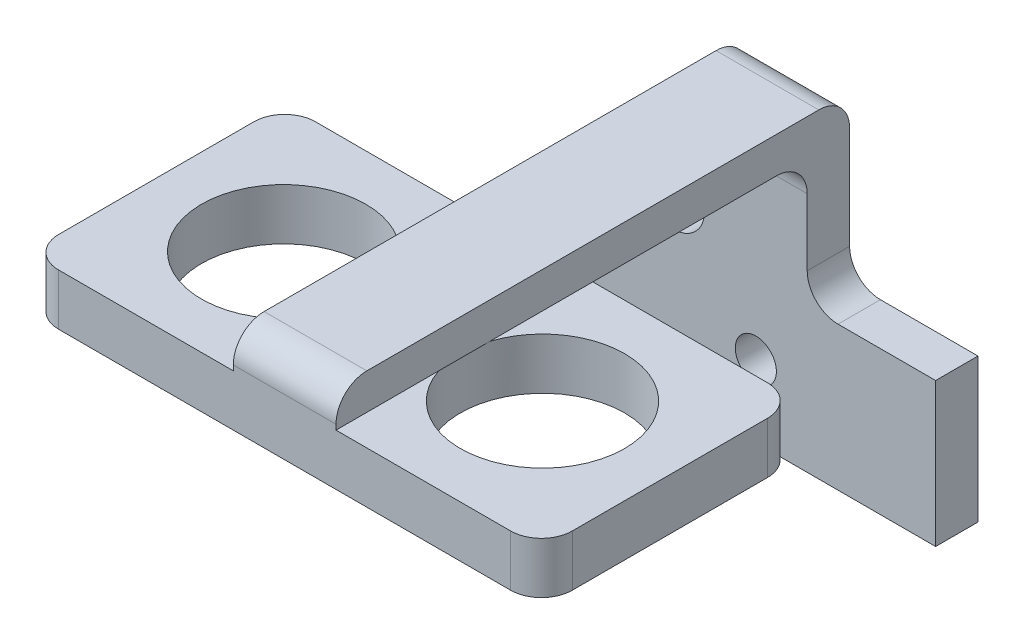
SolidWorks part; units mm, degrees
ref_plane "Front Plane" through (0, 0, 0) normal (0, 0, 1) x (1, 0, 0)
ref_plane "Top Plane" through (0, 0, 0) normal (0, 1, 0) x (1, 0, 0)
ref_plane "Right Plane" through (0, 0, 0) normal (1, 0, 0) x (0, 0, -1)
ref_plane "Plane1" through (0, -5, 0) normal (0, -1, 0) x (1, 0, 0)
sketch "Sketch1" plane through (0, -5, 0) normal (0, -1, 0) x (1, 0, 0)
  line L0 (-25, 12.5) -> (-25, -12.5)
  line L1 (-25, -12.5) -> (25, -12.5)
  line L2 (25, -12.5) -> (25, 12.5)
  line L3 (25, 12.5) -> (-25, 12.5)
extrude "Boss-Extrude1" add sketch "Sketch1" against normal blind 5
sketch "Sketch2" plane through (0, 0, 0) normal (0, 1, 0) x (-1, 0, 0)
  line L0 (5, 12.5) -> (5, -37.5)
  line L1 (5, -37.5) -> (-5, -37.5)
  line L2 (-5, -37.5) -> (-5, 12.5)
  line L3 (-5, 12.5) -> (5, 12.5)
extrude "Boss-Extrude2" add sketch "Sketch2" along normal blind 3.5
sketch "Sketch3" plane through (0, 0, 0) normal (0, -1, 0) x (1, 0, 0)
  line L0 (5, -33.3734) -> (5, -37.5)
  line L1 (5, -37.5) -> (-5, -37.5)
  line L2 (-5, -37.5) -> (-5, -33.3734)
  line L3 (-5, -33.3734) -> (5, -33.3734)
extrude "Boss-Extrude3" add sketch "Sketch3" along normal blind 26.5
sketch "Sketch4" plane through (5, 0, 0) normal (1, 0, 0) x (0, 0, -1)
  line L0 (37.5, -12.5) -> (37.5, -26.5)
  line L1 (37.5, -26.5) -> (33.3734, -26.5)
  line L2 (33.3734, -26.5) -> (33.3734, -12.5)
  line L3 (33.3734, -12.5) -> (37.5, -12.5)
extrude "Boss-Extrude4" add sketch "Sketch4" along normal blind 12.5
sketch "Sketch5" plane through (-5, 0, 0) normal (-1, 0, 0) x (0, 0, 1)
  line L0 (-37.5, -12.5) -> (-33.3734, -12.5)
  line L1 (-33.3734, -12.5) -> (-33.3734, -26.5)
  line L2 (-33.3734, -26.5) -> (-37.5, -26.5)
  line L3 (-37.5, -26.5) -> (-37.5, -12.5)
extrude "Boss-Extrude5" add sketch "Sketch5" along normal blind 12.5
hole_wizard "Ø4.0 (4) Diameter Hole1" positions "Sketch7" profile "Sketch6" hole size "Ø4.0" standard "ANSI Metric"
sketch "Sketch7" plane through (0, 0, -37.5) normal (0, 0, -1) x (-1, 0, 0)
  point P0 (0, -19.5)
sketch "Sketch6" plane through (0, -19.5, -37.5) normal (1, 0, 0) x (0, 1, 0)
  line L0 (0, 0) -> (0, 50)
  line L1 (0, 50) -> (2, 50)
  line L2 (2, 50) -> (2, 0)
  line L5 (2, 0) -> (0, 0)
  line L11 (0, -6.35) -> (0, 107.95) construction
  dimension "Thru Hole Dia." = 4
  dimension "Thru Hole Depth" = 50
hole_wizard "Ø16.0 (16) Diameter Hole1" positions "Sketch9" profile "Sketch8" hole size "Ø16.0" standard "ANSI Metric"
sketch "Sketch9" plane through (0, -5, 0) normal (0, -1, 0) x (1, 0, 0)
  point P0 (-12.6, 0)
  point P1 (-12.6, 0)
sketch "Sketch8" plane through (-12.6, -5, 0) normal (1, 0, 0) x (0, 0, -1)
  line L0 (0, 0) -> (0, 5)
  line L1 (0, 5) -> (8, 5)
  line L2 (8, 5) -> (8, 0)
  line L5 (8, 0) -> (0, 0)
  line L10 (0, 5) -> (-8, 5) construction
  line L11 (0, -6.35) -> (0, 107.95) construction
  dimension "Hole Dia." = 16
  dimension "Hole Depth" = 5
  dimension "Drill Angle" = 180
fillet "Fillet1" radius 3 9 edges at (5, -12.5, -35.4367) (0, 3.5, 12.5) (0, 0, -33.3734) (-25, -2.5, -12.5) (-5, -12.5, -35.4367) (-25, -2.5, 12.5) (0, 3.5, -37.5) (25, -2.5, 12.5) (25, -2.5, -12.5)
mirror "Mirror1" about plane through (0, 0, 0) normal (1, 0, 0) of "Ø16.0 (16) Diameter Hole1"
